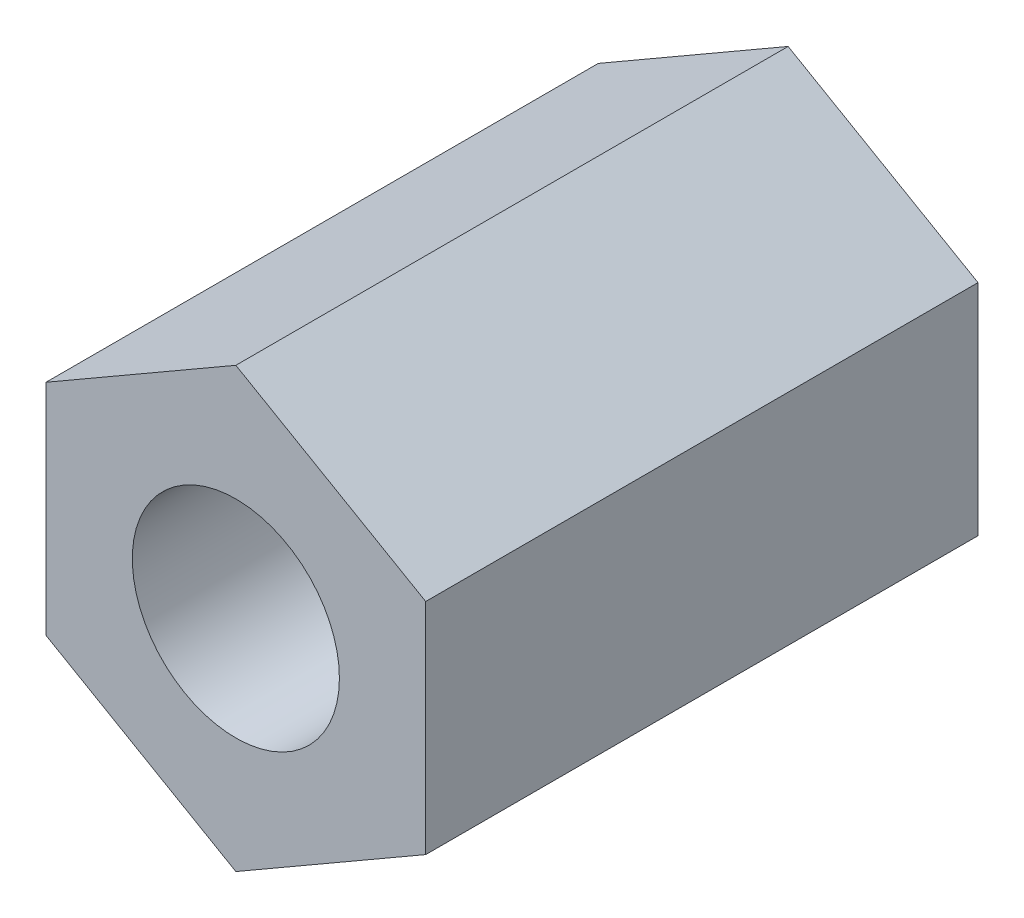
SolidWorks part; units mm, degrees
ref_plane "Plan de face" through (0, 0, 0) normal (0, 0, 1) x (1, 0, 0)
ref_plane "Plan de dessus" through (0, 0, 0) normal (0, 1, 0) x (1, 0, 0)
ref_plane "Plan de droite" through (0, 0, 0) normal (1, 0, 0) x (0, 0, -1)
sketch "Esquisse1" plane through (0, 0, 0) normal (0, 0, 1) x (1, 0, 0)
  line L1 (0, -3.1754) -> (2.75, -1.5877)
  line L2 (2.75, -1.5877) -> (2.75, 1.5877)
  line L3 (2.75, 1.5877) -> (0, 3.1754)
  line L4 (0, 3.1754) -> (-2.75, 1.5877)
  line L5 (-2.75, 1.5877) -> (-2.75, -1.5877)
  line L6 (-2.75, -1.5877) -> (0, -3.1754)
  circle A0 centre (0, 0) radius 2.75 construction
  circle A1 centre (0, 0) radius 1.5
  dimension "D2" = 3
  dimension "D1" = 5.5
extrude "Boss.-Extru.1" add sketch "Esquisse1" along normal blind 8
